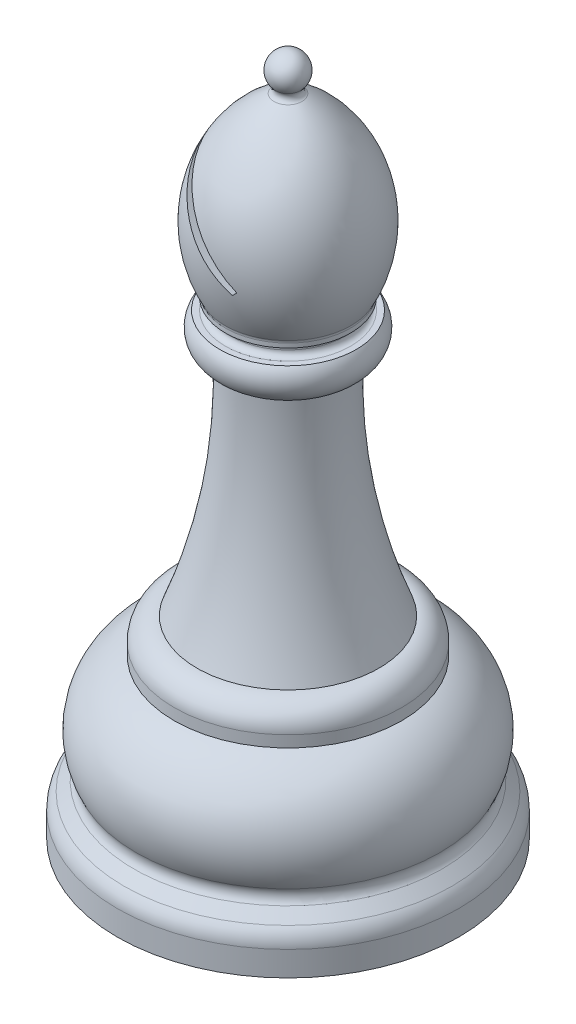
SolidWorks part; units mm, degrees
ref_plane "Front Plane" through (0, 0, 0) normal (0, 0, 1) x (1, 0, 0)
ref_plane "Top Plane" through (0, 0, 0) normal (0, 1, 0) x (1, 0, 0)
ref_plane "Right Plane" through (0, 0, 0) normal (1, 0, 0) x (0, 0, -1)
sketch "Sketch3" plane through (0, 0, 0) normal (0, 0, 1) x (1, 0, 0)
  line L0 (0, 60) -> (0, 0)
  line L1 (0, 0) -> (13, 0)
  line L2 (13, 5) -> (15, 3)
  line L3 (15, 3) -> (15, 0)
  line L4 (15, 0) -> (13, 0)
  line L5 (10, 13.97) -> (10, 14.97)
  line L6 (0, 60) -> (0, 58.5)
  line L7 (6, 40.23) -> (5, 40.23)
  line L10 (5, 40.23) -> (5, 41.23)
  line L11 (5, 41.23) -> (5.5, 41.23)
  line L12 (5.5, 41.23) -> (5.5, 41.73)
  arc A0 (10, 13.97) -> (13, 5) centre (8, 8.3144) cw
  arc A1 (8, 16.97) -> (10, 14.97) centre (8, 14.97) cw
  arc A2 (4.6801, 36.97) -> (8, 16.97) centre (54.6408, 34.9876) ccw
  arc A3 (6, 40.23) -> (4.6801, 36.97) centre (4.457, 38.9575) cw
  arc A9 (0.5291, 57.0964) -> (0, 60) centre (0, 58.5) ccw
  arc A11 (5.5, 41.73) -> (0.5291, 57.0964) centre (-4.3405, 47.0339) ccw
  dimension "D2" = 3
  dimension "D7" = 5.9988
  dimension "D8" = 2
  dimension "D10" = 50
  dimension "D14" = 1.5
  dimension "D15" = 0.5
  dimension "D17" = 0.5
  dimension "D3" = 2
  dimension "D4" = 8.97
  dimension "D5" = 1
  dimension "D6" = 2
  dimension "D9" = 20
  dimension "D11" = 3.26
  dimension "D12" = 16.8664
  dimension "D13" = 2.9036
  dimension "D16" = 60
  dimension "D18" = 1
  dimension "D19" = 1
revolve "Revolve1" add sketch "Sketch3" angle 360 about L0
fillet "Fillet7" radius 2 1 edges at (-15, 3, 0)
fillet "Fillet8" radius 1 1 edges at (-13, 5, 0)
fillet "Fillet9" radius 0.5 1 edges at (-5, 40.23, 0)
fillet "Fillet10" radius 0.5 2 edges at (-5.5, 41.73, 0) (-0.5291, 57.0964, 0)
sketch3d "3DSketch1"
  point P0 (0.9404, 49.4536, 6.5058)
ref_plane "Plane1" through (0, 0, 6.5058) normal (0, 0, 1) x (1, 0, 0)
sketch "Sketch4" plane through (0, 0, 6.5058) normal (0, 0, 1) x (1, 0, 0)
  line L4 (1.6426, 45.4224) -> (1.9726, 45.7525)
  line L6 (1.9726, 45.7525) -> (-6.3085, 54.0402)
  arc A1 (1.6426, 45.4224) -> (-6.3085, 54.0402) centre (17.1457, 67.703) cw
  point P1 (0, 0)
  point P2 (-6.3085, 54.0402)
  point P10 (-1.9522, 49.3473)
extrude "Cut-Extrude3" cut sketch "Sketch4" against normal blind 14 and the other way blind 1
